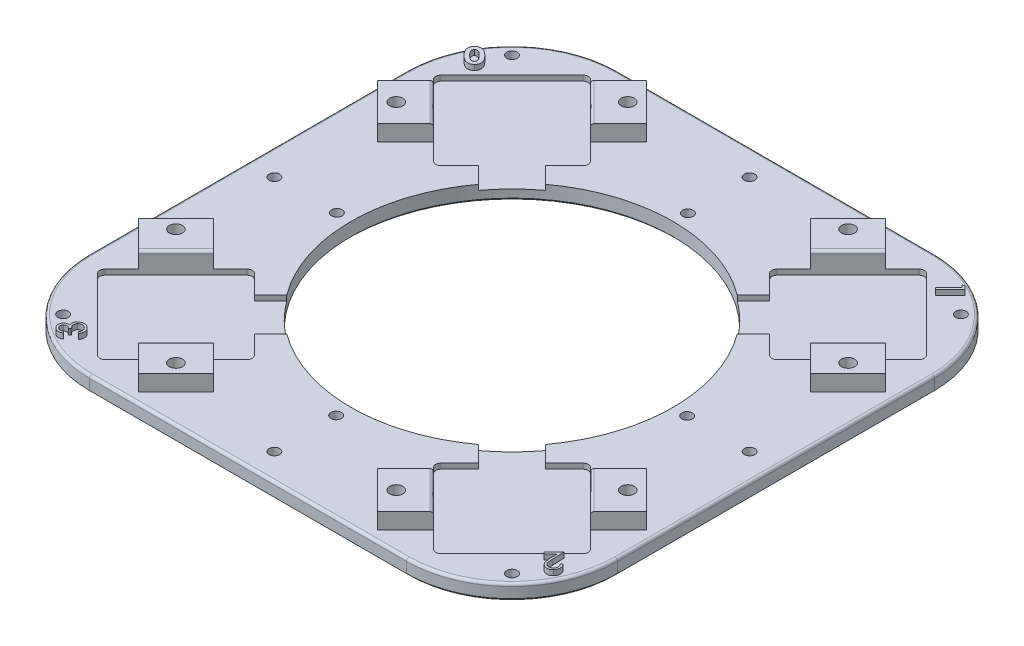
SolidWorks part; units mm, degrees
ref_plane "Спереди" through (0, 0, 0) normal (0, 0, 1) x (1, 0, 0)
ref_plane "Сверху" through (0, 0, 0) normal (0, 1, 0) x (1, 0, 0)
ref_plane "Справа" through (0, 0, 0) normal (1, 0, 0) x (0, 0, -1)
sketch "Эскиз1" plane through (0, 0, 0) normal (0, 1, 0) x (1, 0, 0)
  line L1 (-100, -100) -> (100, -100)
  line L2 (-100, -100) -> (-100, 100)
  line L3 (-100, 100) -> (100, 100)
  line L4 (100, -100) -> (100, 100)
  line L5 (0, 100) -> (0, -100) construction
  line L6 (-100, 0) -> (100, 0) construction
  line L11 (0, 75) -> (0, -75) construction
  line L12 (-39.5, 0) -> (39.5, 0) construction
  line L13 (-85, -85) -> (85, -85) construction
  line L14 (-85, -85) -> (-85, 85) construction
  line L15 (-85, 85) -> (85, 85) construction
  line L16 (85, -85) -> (85, 85) construction
  line L17 (0, 85) -> (0, -85) construction
  line L18 (-85, 0) -> (85, 0) construction
  circle A8 centre (-90, 0) radius 2
  circle A9 centre (0, 90) radius 2
  circle A10 centre (90, 0) radius 2
  circle A11 centre (0, -90) radius 2
  circle A12 centre (-85, 85) radius 2
  circle A13 centre (85, 85) radius 2
  circle A14 centre (85, -85) radius 2
  circle A15 centre (-85, -85) radius 2
  point P0 (0, 0)
  point P4 (0, 0)
  point P11 (0, 0)
  point P27 (0, 0)
  dimension "D6" = 90
  dimension "D1" = 200
  dimension "D8" = 170
  dimension "D7" = 4
extrude "Бобышка-Вытянуть1" add sketch "Эскиз1" along normal blind 6
sketch "Эскиз2" plane through (0, 6, 0) normal (0, 1, 0) x (1, 0, 0)
  line L0 (0, 72.2532) -> (0, 0) construction
  line L1 (0, 0) -> (100, 100) construction
  line L2 (63.6396, 33.9411) -> (33.9411, 63.6396)
  line L3 (63.6396, 33.9411) -> (93.3381, 63.6396)
  line L4 (33.9411, 63.6396) -> (63.6396, 93.3381)
  line L5 (93.3381, 63.6396) -> (63.6396, 93.3381)
  line L6 (63.6396, 33.9411) -> (63.6396, 93.3381) construction
  line L7 (33.9411, 63.6396) -> (93.3381, 63.6396) construction
  line L8 (33.9411, -63.6396) -> (63.6396, -33.9411)
  line L9 (33.9411, -63.6396) -> (63.6396, -93.3381)
  line L10 (63.6396, -93.3381) -> (93.3381, -63.6396)
  line L11 (63.6396, -33.9411) -> (93.3381, -63.6396)
  line L12 (-63.6396, -33.9411) -> (-33.9411, -63.6396)
  line L13 (-63.6396, -33.9411) -> (-93.3381, -63.6396)
  line L14 (-93.3381, -63.6396) -> (-63.6396, -93.3381)
  line L15 (-33.9411, -63.6396) -> (-63.6396, -93.3381)
  line L16 (-33.9411, 63.6396) -> (-63.6396, 33.9411)
  line L17 (-33.9411, 63.6396) -> (-63.6396, 93.3381)
  line L18 (-63.6396, 93.3381) -> (-93.3381, 63.6396)
  line L19 (-63.6396, 33.9411) -> (-93.3381, 63.6396)
  line L20 (0, 0) -> (119.0497, 0) construction
  point P6 (63.6396, 63.6396)
  point P24 (0, 0)
  dimension "D1" = 42
  dimension "D2" = 90
  dimension "D4" = 63.6396
  dimension "D5" = 63.6396
  dimension "D3" = 4
extrude "Вырез-Вытянуть1" cut sketch "Эскиз2" against normal blind 2
fillet "Скругление1" radius 2 16 edges at (63.6396, 5, -33.9411) (33.9411, 5, -63.6396) (93.3381, 5, -63.6396) (63.6396, 5, -93.3381) (-63.6396, 5, -93.3381) (-63.6396, 5, -33.9411) (-93.3381, 5, -63.6396) (-33.9411, 5, -63.6396) (63.6396, 5, 93.3381) (93.3381, 5, 63.6396) (63.6396, 5, 33.9411) (33.9411, 5, 63.6396) (-63.6396, 5, 93.3381) (-33.9411, 5, 63.6396) (-63.6396, 5, 33.9411) (-93.3381, 5, 63.6396)
sketch "Эскиз3" plane through (0, 6, 0) normal (0, 1, 0) x (1, 0, 0)
  line L0 (48.7904, 48.7904) -> (67.3817, 67.3817) construction
  line L1 (35.3553, 62.2254) -> (62.2254, 35.3553) construction
  line L2 (48.7904, 78.4889) -> (78.4889, 48.7904) construction
  line L3 (62.2254, 91.9239) -> (35.3553, 65.0538) construction
  line L4 (65.0538, 35.3553) -> (91.9239, 62.2254) construction
  line L5 (41.7193, 71.4178) -> (55.8614, 85.5599)
  line L6 (41.7193, 71.4178) -> (31.1127, 82.0244)
  line L7 (55.8614, 85.5599) -> (45.2548, 96.1665)
  line L8 (31.1127, 82.0244) -> (45.2548, 96.1665)
  line L9 (62.2254, 91.9239) -> (35.3553, 65.0538) construction
  line L10 (85.5599, 55.8614) -> (96.1665, 45.2548)
  line L11 (82.0244, 31.1127) -> (96.1665, 45.2548)
  line L12 (71.4178, 41.7193) -> (82.0244, 31.1127)
  line L13 (71.4178, 41.7193) -> (85.5599, 55.8614)
  line L44 (65.0538, 35.3553) -> (91.9239, 62.2254) construction
  line L45 (0, 128.3294) -> (0, 0) construction
  line L64 (0, 0) -> (145.1139, 0) construction
  line L65 (62.2254, 91.9239) -> (35.3553, 65.0538) construction
  line L90 (48.7904, -78.4889) -> (78.4889, -48.7904) construction
  line L91 (48.7904, -48.7904) -> (67.3817, -67.3817) construction
  line L92 (71.4178, -41.7193) -> (85.5599, -55.8614)
  line L93 (71.4178, -41.7193) -> (82.0244, -31.1127)
  line L94 (82.0244, -31.1127) -> (96.1665, -45.2548)
  line L95 (85.5599, -55.8614) -> (96.1665, -45.2548)
  line L96 (31.1127, -82.0244) -> (45.2548, -96.1665)
  line L97 (55.8614, -85.5599) -> (45.2548, -96.1665)
  line L98 (41.7193, -71.4178) -> (31.1127, -82.0244)
  line L99 (41.7193, -71.4178) -> (55.8614, -85.5599)
  line L100 (-48.7904, -48.7904) -> (-67.3817, -67.3817) construction
  line L101 (-48.7904, -78.4889) -> (-78.4889, -48.7904) construction
  line L102 (-48.7904, 78.4889) -> (-78.4889, 48.7904) construction
  line L103 (-48.7904, 48.7904) -> (-67.3817, 67.3817) construction
  line L104 (-41.7193, -71.4178) -> (-55.8614, -85.5599)
  line L105 (-41.7193, -71.4178) -> (-31.1127, -82.0244)
  line L106 (-55.8614, -85.5599) -> (-45.2548, -96.1665)
  line L107 (-31.1127, -82.0244) -> (-45.2548, -96.1665)
  line L108 (-85.5599, -55.8614) -> (-96.1665, -45.2548)
  line L109 (-82.0244, -31.1127) -> (-96.1665, -45.2548)
  line L110 (-71.4178, -41.7193) -> (-82.0244, -31.1127)
  line L111 (-71.4178, -41.7193) -> (-85.5599, -55.8614)
  line L112 (-71.4178, 41.7193) -> (-85.5599, 55.8614)
  line L113 (-71.4178, 41.7193) -> (-82.0244, 31.1127)
  line L114 (-82.0244, 31.1127) -> (-96.1665, 45.2548)
  line L115 (-85.5599, 55.8614) -> (-96.1665, 45.2548)
  line L116 (-31.1127, 82.0244) -> (-45.2548, 96.1665)
  line L117 (-55.8614, 85.5599) -> (-45.2548, 96.1665)
  line L118 (-41.7193, 71.4178) -> (-31.1127, 82.0244)
  line L119 (-41.7193, 71.4178) -> (-55.8614, 85.5599)
  point P16 (48.7904, 78.4889)
  dimension "D1" = 20
  dimension "D2" = 15
extrude "Бобышка-Вытянуть3" add sketch "Эскиз3" along normal blind 6
fillet "Скругление4" radius 40 4 edges at (100, 3, -100) (100, 3, 100) (-100, 3, 100) (-100, 3, -100)
sketch "Эскиз4" plane through (0, 12, 0) normal (0, 1, 0) x (1, 0, 0)
  line L0 (89.0955, 38.1838) -> (38.1838, 89.0955) construction
  line L1 (82.0244, 31.1127) -> (96.1665, 45.2548) construction
  line L2 (45.2548, 96.1665) -> (31.1127, 82.0244) construction
  line L3 (41.7193, 71.4178) -> (55.8614, 85.5599) construction
  line L4 (48.7904, 48.7904) -> (78.4889, 78.4889) construction
  line L5 (35.3553, 62.2254) -> (62.2254, 35.3553) construction
  line L6 (91.9239, 65.0538) -> (65.0538, 91.9239) construction
  line L7 (0, 119.2498) -> (0, 0) construction
  line L8 (0, 0) -> (156.895, 0) construction
  line L9 (48.7904, -48.7904) -> (78.4889, -78.4889) construction
  line L10 (89.0955, -38.1838) -> (38.1838, -89.0955) construction
  line L11 (-89.0955, -38.1838) -> (-38.1838, -89.0955) construction
  line L12 (-48.7904, -48.7904) -> (-78.4889, -78.4889) construction
  line L13 (-48.7904, 48.7904) -> (-78.4889, 78.4889) construction
  line L14 (-89.0955, 38.1838) -> (-38.1838, 89.0955) construction
  circle A0 centre (41.7193, 85.5599) radius 2.5
  circle A1 centre (85.5599, 41.7193) radius 2.5
  circle A14 centre (85.5599, -41.7193) radius 2.5
  circle A15 centre (41.7193, -85.5599) radius 2.5
  circle A16 centre (-41.7193, -85.5599) radius 2.5
  circle A17 centre (-85.5599, -41.7193) radius 2.5
  circle A18 centre (-85.5599, 41.7193) radius 2.5
  circle A19 centre (-41.7193, 85.5599) radius 2.5
  dimension "D1" = 10
  dimension "D3" = 62
extrude "Вырез-Вытянуть2" cut sketch "Эскиз4" against normal blind 8
sketch "Эскиз7" plane through (0, 6, 0) normal (0, 1, 0) x (1, 0, 0)
  line L0 (0, 76.3028) -> (0, 0) construction
  line L1 (0, 0) -> (74.3797, 74.3797) construction
  line L2 (20, 6) -> (60, 6)
  line L3 (-6, 20) -> (6, 20)
  line L4 (-6, 20) -> (-6, 60)
  line L5 (-6, 60) -> (6, 60)
  line L6 (6, 20) -> (6, 60)
  line L7 (0, 60) -> (0, 20) construction
  line L8 (-6, 40) -> (6, 40) construction
  line L9 (20, 6) -> (20, -6)
  line L10 (20, -6) -> (60, -6)
  line L11 (60, 6) -> (60, -6)
  line L12 (6, -20) -> (6, -60)
  line L13 (6, -20) -> (-6, -20)
  line L14 (-6, -20) -> (-6, -60)
  line L15 (6, -60) -> (-6, -60)
  line L16 (-20, -6) -> (-60, -6)
  line L17 (-20, -6) -> (-20, 6)
  line L18 (-20, 6) -> (-60, 6)
  line L19 (-60, -6) -> (-60, 6)
  circle A0 centre (28.2843, 28.2843) radius 12
  circle A1 centre (28.2843, -28.2843) radius 12
  circle A2 centre (-28.2843, -28.2843) radius 12
  circle A3 centre (-28.2843, 28.2843) radius 12
  point P6 (0, 40)
  point P15 (0, 0)
  point P32 (0, 0)
  dimension "D1" = 40
  dimension "D2" = 24
  dimension "D4" = 12
  dimension "D5" = 40
  dimension "D6" = 40
  dimension "D3" = 4
  dimension "D7" = 4
extrude "Вырез-Вытянуть3" cut sketch "Эскиз7" against normal blind 6
sketch "Эскиз8" plane through (0, 6, 0) normal (0, 1, 0) x (1, 0, 0)
  line L0 (48.7904, 48.7904) -> (72.3205, 72.3205) construction
  line L1 (35.3553, 62.2254) -> (62.2254, 35.3553) construction
  line L2 (44.5477, 31.8198) -> (31.8198, 44.5477)
  line L3 (44.5477, 31.8198) -> (65.7609, 53.033)
  line L4 (31.8198, 44.5477) -> (53.033, 65.7609)
  line L5 (65.7609, 53.033) -> (53.033, 65.7609)
  line L6 (44.5477, 31.8198) -> (53.033, 65.7609) construction
  line L7 (31.8198, 44.5477) -> (65.7609, 53.033) construction
  line L20 (0, 107.5006) -> (0, 0) construction
  line L21 (0, 0) -> (140.6034, 0) construction
  line L22 (31.8198, -44.5477) -> (65.7609, -53.033) construction
  line L23 (44.5477, -31.8198) -> (53.033, -65.7609) construction
  line L24 (48.7904, -48.7904) -> (72.3205, -72.3205) construction
  line L25 (65.7609, -53.033) -> (53.033, -65.7609)
  line L26 (31.8198, -44.5477) -> (53.033, -65.7609)
  line L27 (44.5477, -31.8198) -> (65.7609, -53.033)
  line L28 (44.5477, -31.8198) -> (31.8198, -44.5477)
  line L29 (-48.7904, -48.7904) -> (-72.3205, -72.3205) construction
  line L30 (-44.5477, -31.8198) -> (-53.033, -65.7609) construction
  line L31 (-31.8198, -44.5477) -> (-65.7609, -53.033) construction
  line L32 (-31.8198, 44.5477) -> (-65.7609, 53.033) construction
  line L33 (-44.5477, 31.8198) -> (-53.033, 65.7609) construction
  line L34 (-48.7904, 48.7904) -> (-72.3205, 72.3205) construction
  line L35 (-44.5477, -31.8198) -> (-31.8198, -44.5477)
  line L36 (-44.5477, -31.8198) -> (-65.7609, -53.033)
  line L37 (-31.8198, -44.5477) -> (-53.033, -65.7609)
  line L38 (-65.7609, -53.033) -> (-53.033, -65.7609)
  line L39 (-65.7609, 53.033) -> (-53.033, 65.7609)
  line L40 (-31.8198, 44.5477) -> (-53.033, 65.7609)
  line L41 (-44.5477, 31.8198) -> (-65.7609, 53.033)
  line L42 (-44.5477, 31.8198) -> (-31.8198, 44.5477)
  point P24 (0, 16.9706)
  dimension "D1" = 18
  dimension "D2" = 30
extrude "Вырез-Вытянуть4" cut sketch "Эскиз8" against normal blind 2 contours L2 L3 L5 L4
fillet "Скругление6" radius 1 8 edges at (78.4889, 12, -48.7904) (48.7904, 12, -78.4889) (-78.4889, 12, 48.7904) (-48.7904, 12, 78.4889) (48.7904, 12, 78.4889) (78.4889, 12, 48.7904) (-78.4889, 12, -48.7904) (-48.7904, 12, -78.4889)
sketch "Эскиз9" plane through (0, 6, 0) normal (0, 1, 0) x (1, 0, 0)
  line L0 (-70.7105, 0.151) -> (0.151, 70.7105) construction
  line L1 (-70.7105, 0.151) -> (-0.151, -70.7105) construction
  line L2 (0.151, 70.7105) -> (70.7105, -0.151) construction
  line L3 (-0.151, -70.7105) -> (70.7105, -0.151) construction
  line L4 (-70.7105, 0.151) -> (70.7105, -0.151) construction
  line L5 (0.151, 70.7105) -> (-0.151, -70.7105) construction
  line L6 (0, 0) -> (60.8554, 60.8554) construction
  circle A0 centre (0.1419, 66.4679) radius 2
  circle A4 centre (-0.1419, -66.4679) radius 2
  circle A5 centre (66.4679, -0.1419) radius 2
  circle A6 centre (-66.4679, 0.1419) radius 2
  point P1 (0, 0)
  dimension "D2" = 4
  dimension "D3" = 3
  dimension "D4" = 3
  dimension "D5" = 94
  dimension "D1" = 100
extrude "Вырез-Вытянуть5" cut sketch "Эскиз9" against normal blind 10
sketch "Эскиз10" plane through (0, 6, 0) normal (0, 1, 0) x (1, 0, 0)
  line L0 (-89.4334, 70.8427) -> (-83.9454, 76.3307) construction
  line L1 (0, 108.5259) -> (0, 0) construction
  line L2 (71.3984, 88.9173) -> (76.8147, 83.501) construction
  line L3 (90.0364, -69.9365) -> (84.274, -75.6989) construction
  line L4 (-72.0522, -89.0668) -> (-79.6906, -81.6618) construction
  text T0 "<b>0</b>\r\n" font "Century Gothic" height 8
  text T1 "1\r\n" font "Century Gothic" height 8
  text T2 "2" font "Century Gothic" height 8
  text T3 "3\r\n" font "Century Gothic" height 8
extrude "Бобышка-Вытянуть6" add sketch "Эскиз10" along normal blind 2
fillet "Скругление9" radius 1 8 edges at (88.2843, 6, 88.2843) (0, 6, 100) (-88.2843, 6, 88.2843) (-100, 6, 0) (-88.2843, 6, -88.2843) (0, 6, -100) (88.2843, 6, -88.2843) (100, 6, 0)
sketch "Эскиз11" plane through (0, 6, 0) normal (0, 1, 0) x (1, 0, 0)
  circle A0 centre (0, 0) radius 61
extrude "Вырез-Вытянуть6" cut sketch "Эскиз11" against normal through all both and the other way through all
chamfer "Фаска1" distance 1 angle 45 21 edges at (100, 0, 0) (88.2843, 0, -88.2843) (88.2843, 0, 88.2843) (0, 0, -100) (0, 0, 100) (-88.2843, 0, -88.2843) (-88.2843, 0, 88.2843) (-100, 0, 0) (-85, 0, 87) (85, 0, -83) (-90, 0, 2) (90, 0, 2) (0, 0, -88) (0, 0, 92) (-85, 0, -83) (85, 0, 87) (-66.4679, 0, -2.1419) (66.4679, 0, -1.8581) (-0.1419, 0, 64.4679) (0.1419, 0, -68.4679) (0, 0, 61)
